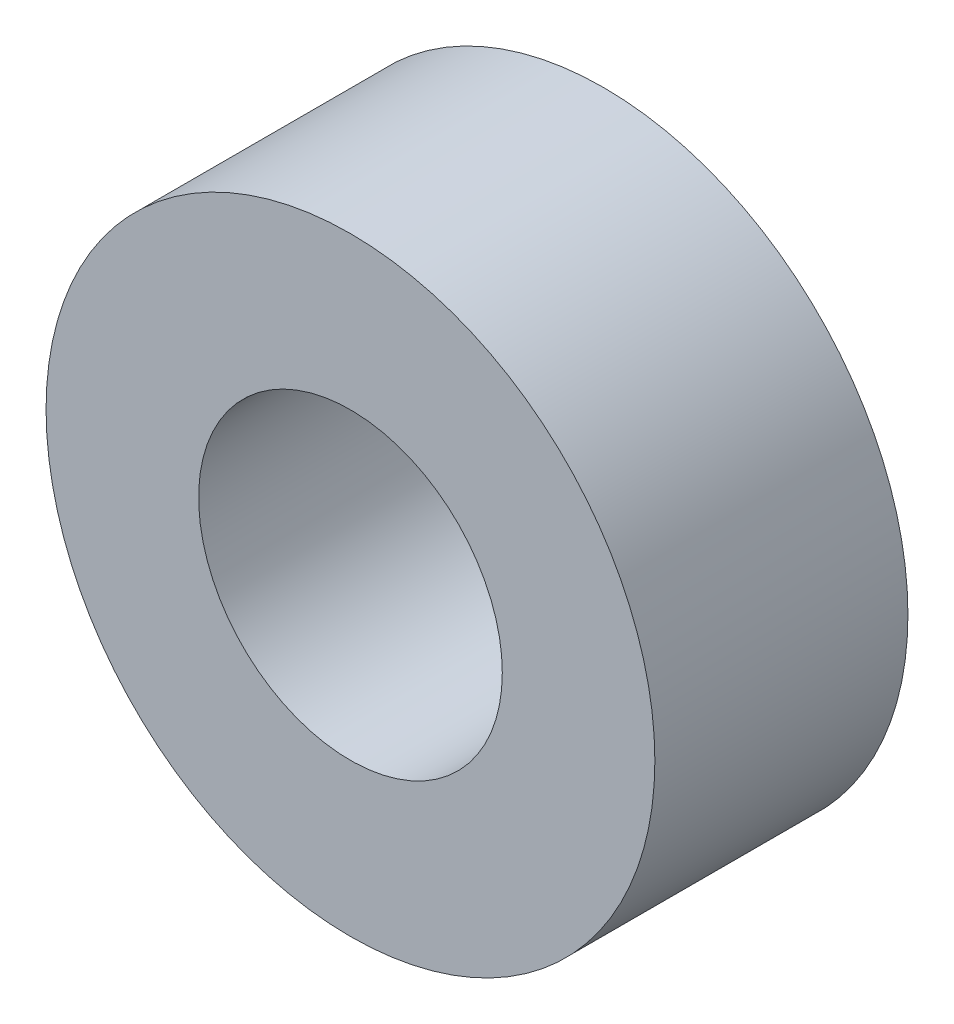
SolidWorks part; units mm, degrees
ref_plane "前视基准面" through (0, 0, 0) normal (0, 0, 1) x (1, 0, 0)
ref_plane "上视基准面" through (0, 0, 0) normal (0, 1, 0) x (1, 0, 0)
ref_plane "右视基准面" through (0, 0, 0) normal (1, 0, 0) x (0, 0, -1)
sketch "草图2" plane through (0, 0, 0) normal (0, 0, 1) x (1, 0, 0)
  circle A0 centre (0, 0) radius 1.5
  circle A1 centre (0, 0) radius 3.0071
extrude "凸台-拉伸1" add sketch "草图2" along normal blind 2.5
sketch "草图3" plane through (0, 0, 0) normal (0, 0, -1) x (-1, 0, 0)
  line L0 (0, 0) -> (0, -3.0071)
  circle A0 centre (0, 0) radius 3.0071 construction
